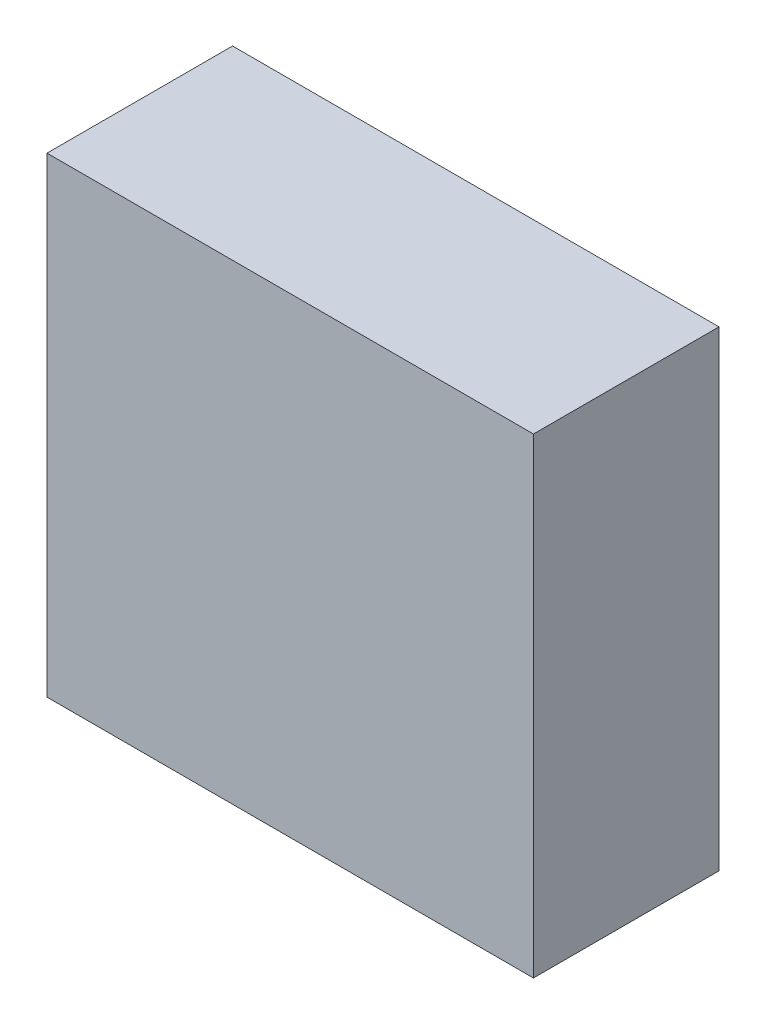
SolidWorks part; units mm, degrees
ref_plane "Plan de face" through (0, 0, 0) normal (0, 0, 1) x (1, 0, 0)
ref_plane "Plan de dessus" through (0, 0, 0) normal (0, 1, 0) x (1, 0, 0)
ref_plane "Plan de droite" through (0, 0, 0) normal (1, 0, 0) x (0, 0, -1)
sketch "Esquisse1" plane through (0, 0, 0) normal (0, 0, 1) x (1, 0, 0)
  line L0 (-26.2141, 25.3893) -> (0, 25.3893)
  line L1 (0, 25.3893) -> (0, 0)
  line L2 (0, 0) -> (-26.2141, 0)
  line L3 (-26.2141, 0) -> (-26.2141, 25.3893)
extrude "Boss.-Extru.1" add sketch "Esquisse1" along normal blind 10
